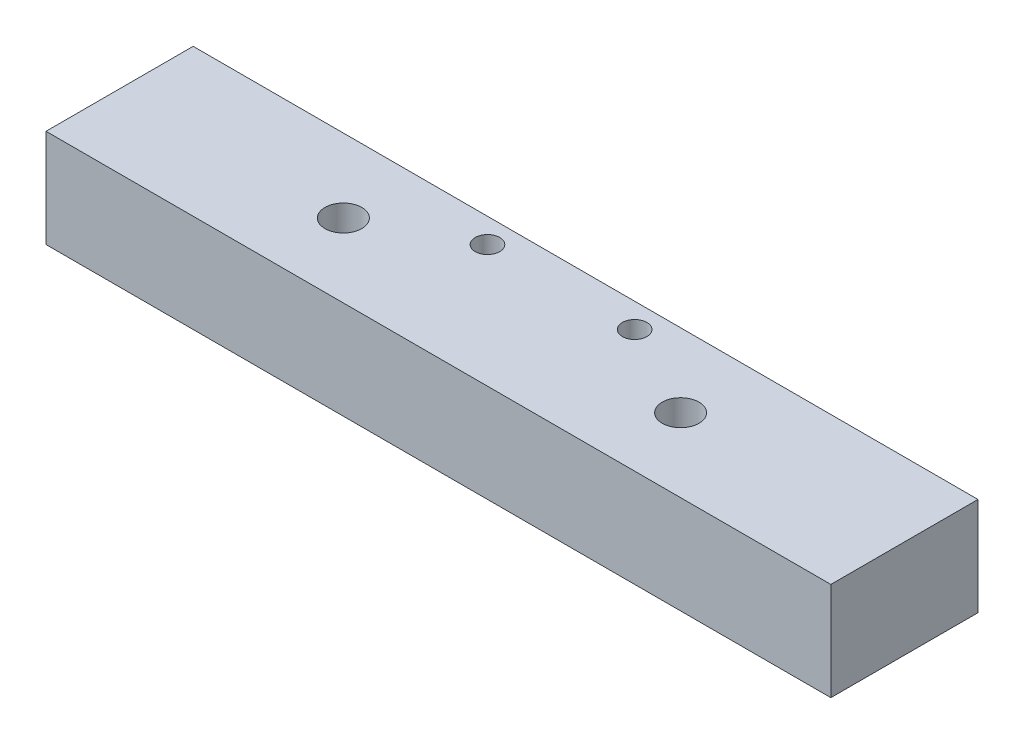
SolidWorks part; units mm, degrees
material "Balsa"
ref_plane "Front Plane" through (0, 0, 0) normal (0, 0, 1) x (1, 0, 0)
ref_plane "Top Plane" through (0, 0, 0) normal (0, 1, 0) x (1, 0, 0)
ref_plane "Right Plane" through (0, 0, 0) normal (1, 0, 0) x (0, 0, -1)
sketch "Sketch1" plane through (0, 0, 0) normal (0, 1, 0) x (1, 0, 0)
  line L1 (-203.2, -38.1) -> (203.2, -38.1)
  line L2 (-203.2, -38.1) -> (-203.2, 38.1)
  line L3 (-203.2, 38.1) -> (203.2, 38.1)
  line L4 (203.2, -38.1) -> (203.2, 38.1)
  line L5 (0, 38.1) -> (0, -38.1) construction
  line L6 (-203.2, 0) -> (203.2, 0) construction
  point P0 (0, 0)
  dimension "D1" = 406.4
  dimension "D2" = 76.2
extrude "Boss-Extrude1" add sketch "Sketch1" along normal blind 50.8
ref_plane "Plane1" through (0, 0, 0) normal (1, 0, 0) x (0, 0, -1)
sketch "Sketch3" plane through (0, 50.8, 0) normal (0, 1, 0) x (1, 0, 0)
  line L0 (0, -27.94) -> (0, 27.94) construction
  circle A0 centre (87.3125, 0) radius 9.525
  dimension "D1" = 87.3125
  dimension "D2" = 19.05
extrude "Cut-Extrude1" cut sketch "Sketch3" against normal blind 50.8
sketch "Sketch4" plane through (0, 50.8, 0) normal (0, 1, 0) x (1, 0, 0)
  line L0 (0, -27.94) -> (0, 27.94) construction
  circle A0 centre (38.1, 25.4) radius 6.35
  circle A1 centre (87.3125, 0) radius 9.525 construction
  dimension "D1" = 12.7
  dimension "D2" = 25.4
  dimension "D3" = 38.1
extrude "Cut-Extrude2" cut sketch "Sketch4" against normal blind 8.89
mirror "Mirror1" about plane through (0, 0, 0) normal (1, 0, 0) of "Cut-Extrude2", "Cut-Extrude1"
